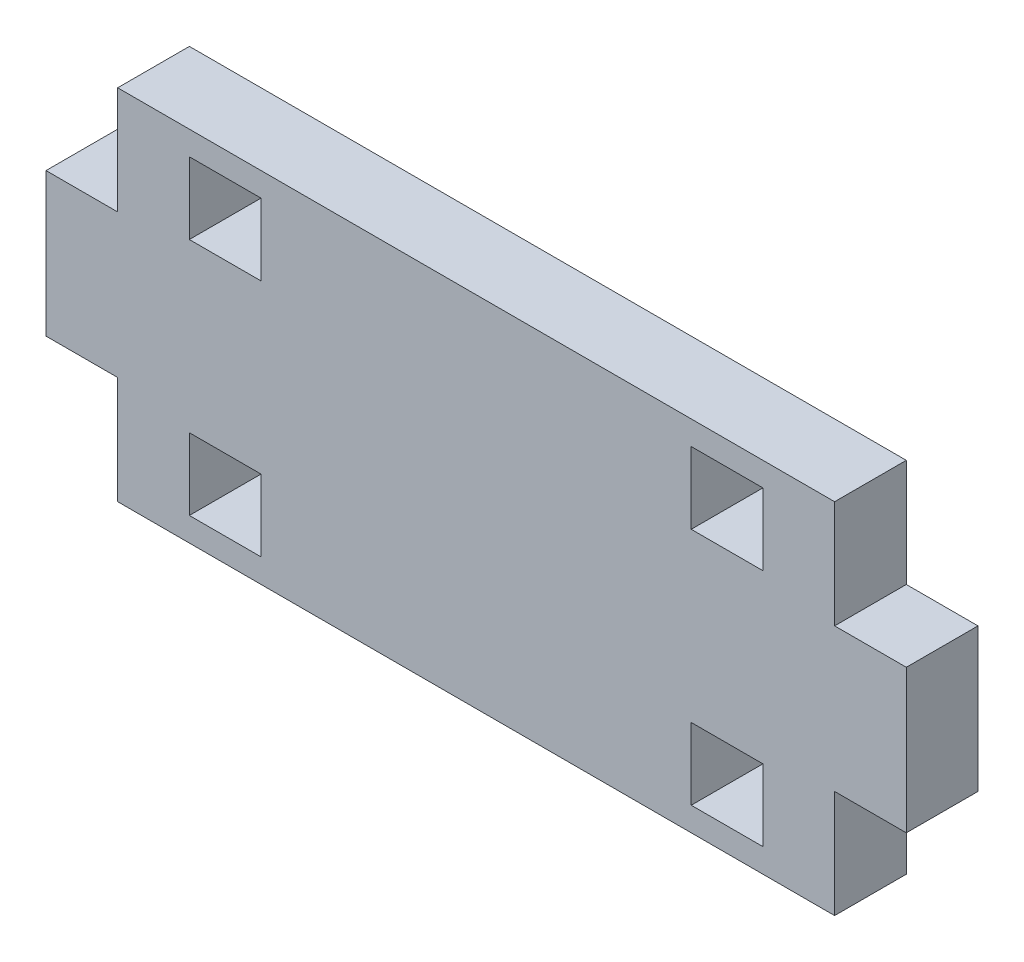
SolidWorks part; units mm, degrees
ref_plane "Front Plane" through (0, 0, 0) normal (0, 0, 1) x (1, 0, 0)
ref_plane "Top Plane" through (0, 0, 0) normal (0, 1, 0) x (1, 0, 0)
ref_plane "Right Plane" through (0, 0, 0) normal (1, 0, 0) x (0, 0, -1)
sketch "Sketch1" plane through (0, 0, 0) normal (0, 0, 1) x (1, 0, 0)
  line L0 (-16, 3.4986) -> (-13, 3.4986)
  line L1 (-13, 7.9986) -> (17, 7.9986)
  line L2 (-16, 3.4986) -> (-16, -2.5014)
  line L3 (-13, -7.0014) -> (17, -7.0014)
  line L4 (20, 3.4986) -> (20, -2.5014)
  line L5 (-13, 3.4986) -> (-13, 7.9986)
  line L6 (-16, -2.5014) -> (-13, -2.5014)
  line L7 (-13, -2.5014) -> (-13, -7.0014)
  line L8 (-10.002, 13.0484) -> (-10.002, -9.5659) construction
  line L9 (-10.002, 6.9986) -> (-10.002, 3.9986)
  line L10 (-10.002, 6.9986) -> (-7.002, 6.9986)
  line L11 (-10.002, 3.9986) -> (-7.002, 3.9986)
  line L12 (-7.002, 6.9986) -> (-7.002, 3.9986)
  line L13 (-10.002, -3.0014) -> (-10.002, -6.0014)
  line L14 (-10.002, -3.0014) -> (-7.002, -3.0014)
  line L15 (-10.002, -6.0014) -> (-7.002, -6.0014)
  line L16 (-7.002, -3.0014) -> (-7.002, -6.0014)
  line L17 (17, 7.9986) -> (17, 3.4986)
  line L18 (17, 3.4986) -> (20, 3.4986)
  line L19 (20, -2.5014) -> (17, -2.5014)
  line L20 (17, -2.5014) -> (17, -7.0014)
  line L21 (2, 7.9986) -> (2, -11.5687) construction
  line L22 (14, 6.9986) -> (14, 3.9986)
  line L23 (14, 6.9986) -> (11, 6.9986)
  line L24 (14, 3.9986) -> (11, 3.9986)
  line L25 (11, 6.9986) -> (11, 3.9986)
  line L26 (14, -6.0014) -> (14, -3.0014)
  line L27 (14, -6.0014) -> (11, -6.0014)
  line L28 (14, -3.0014) -> (11, -3.0014)
  line L29 (11, -6.0014) -> (11, -3.0014)
  line L30 (14, 13.0484) -> (14, -10.2211) construction
  point P0 (0, 0)
  point P11 (-14.5, -2.5014)
  point P13 (-7.002, 5.4986)
  point P20 (-16, 0.4986)
  point P23 (-7.002, -4.5014)
  dimension "D1" = 5.998
  dimension "D2" = 3
  dimension "D3" = 6
  dimension "D4" = 4.5
  dimension "D5" = 3
  dimension "D6" = 3
  dimension "D7" = 3
  dimension "D8" = 5
  dimension "D9" = 5
  dimension "D10" = 36
  dimension "D11" = 3
  dimension "D12" = 4.5
  dimension "D13" = 4.5
  dimension "D14" = 3
  dimension "D15" = 3
  dimension "D16" = 3
  dimension "D17" = 3
  dimension "D18" = 3
  dimension "D19" = 3
extrude "Boss-Extrude1" add sketch "Sketch1" along normal blind 3
